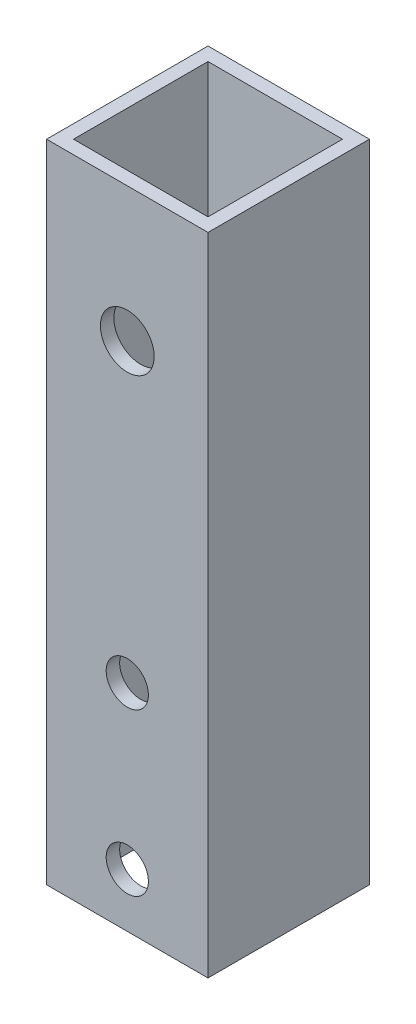
SolidWorks part; units mm, degrees
material "6061-T6 (SS)"
ref_plane "Front Plane" through (0, 0, 0) normal (0, 0, 1) x (1, 0, 0)
ref_plane "Top Plane" through (0, 0, 0) normal (0, 1, 0) x (1, 0, 0)
ref_plane "Right Plane" through (0, 0, 0) normal (1, 0, 0) x (0, 0, -1)
sketch "Sketch1" plane through (0, 0, 0) normal (0, 1, 0) x (1, 0, 0)
  line L0 (-7.9375, 7.9375) -> (7.9375, 7.9375)
  line L1 (-9.525, -9.525) -> (9.525, -9.525)
  line L2 (-9.525, -9.525) -> (-9.525, 9.525)
  line L3 (-9.525, 9.525) -> (9.525, 9.525)
  line L4 (9.525, -9.525) -> (9.525, 9.525)
  line L5 (-9.525, -9.525) -> (9.525, 9.525) construction
  line L6 (-9.525, 9.525) -> (9.525, -9.525) construction
  line L7 (7.9375, -7.9375) -> (7.9375, 7.9375)
  line L8 (-7.9375, -7.9375) -> (7.9375, -7.9375)
  line L9 (-7.9375, -7.9375) -> (-7.9375, 7.9375)
  point P0 (0, 0)
  dimension "D1" = 19.05
  dimension "D2" = 1.5875
extrude "Boss-Extrude1" add sketch "Sketch1" along normal blind 76.2
sketch "Sketch2" plane through (0, 0, 9.525) normal (0, 0, 1) x (1, 0, 0)
  line L0 (0, 0) -> (0, 6.35) construction
  line L1 (-9.525, 0) -> (9.525, 0) construction
  line L2 (-9.525, 31.75) -> (9.525, 31.75) construction
  line L3 (-9.525, 76.2) -> (-9.525, 0) construction
  line L4 (9.525, 76.2) -> (9.525, 0) construction
  line L5 (0, 31.75) -> (0, 25.4) construction
  circle A0 centre (0, 6.35) radius 2.4892
  circle A1 centre (0, 25.4) radius 2.4892
  circle A2 centre (0, 60.325) radius 3.175
  dimension "D1" = 4.9784
  dimension "D3" = 6.35
  dimension "D5" = 60.325
  dimension "D2" = 31.75
  dimension "D4" = 6.35
extrude "Cut-Extrude1" cut sketch "Sketch2" against normal through all
